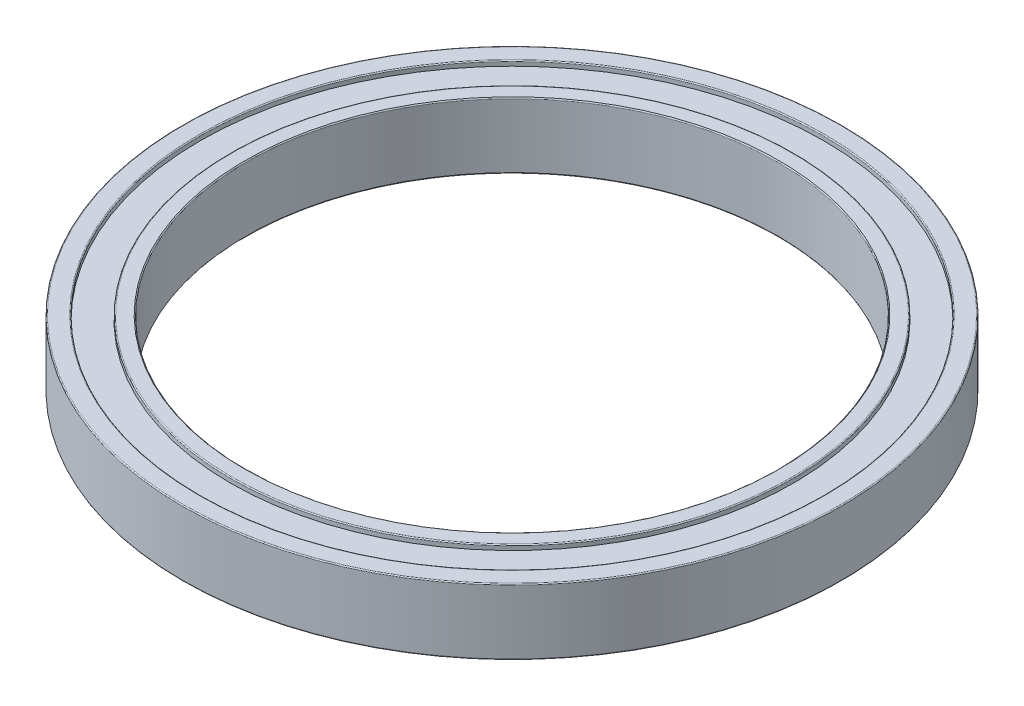
SolidWorks part; units mm, degrees
ref_plane "前视基准面" through (0, 0, 0) normal (0, 0, 1) x (1, 0, 0)
ref_plane "上视基准面" through (0, 0, 0) normal (0, 1, 0) x (1, 0, 0)
ref_plane "右视基准面" through (0, 0, 0) normal (1, 0, 0) x (0, 0, -1)
sketch "草图1" plane through (0, 0, 0) normal (0, 1, 0) x (1, 0, 0)
  circle A0 centre (0, 0) radius 52.5
  circle A1 centre (0, 0) radius 65
  dimension "D1" = 105
  dimension "D2" = 130
extrude "凸台-拉伸1" add sketch "草图1" along normal blind 13
sketch "草图2" plane through (0, 13, 0) normal (0, 1, 0) x (1, 0, 0)
  circle A0 centre (0, 0) radius 61.5
  circle A1 centre (0, 0) radius 55.5
  circle A2 centre (0, 0) radius 52.5 construction
  dimension "D1" = 6
  dimension "D2" = 3
extrude "切除-拉伸1" cut sketch "草图2" against normal blind 1
fillet "圆角1" radius 0.2 4 edges at (0, 13, 52.5) (0, 13, 55.5) (0, 13, 61.5) (0, 13, 65)
ref_plane "基准面1" through (0, 6.5, 0) normal (0, -1, 0) x (-1, 0, 0)
mirror "镜向3" about plane through (0, 6.5, 0) normal (0, -1, 0) of "切除-拉伸1"
fillet "圆角2" radius 0.2 4 edges at (0, 0, 61.5) (0, 0, 52.5) (0, 0, 55.5) (0, 0, 65)
